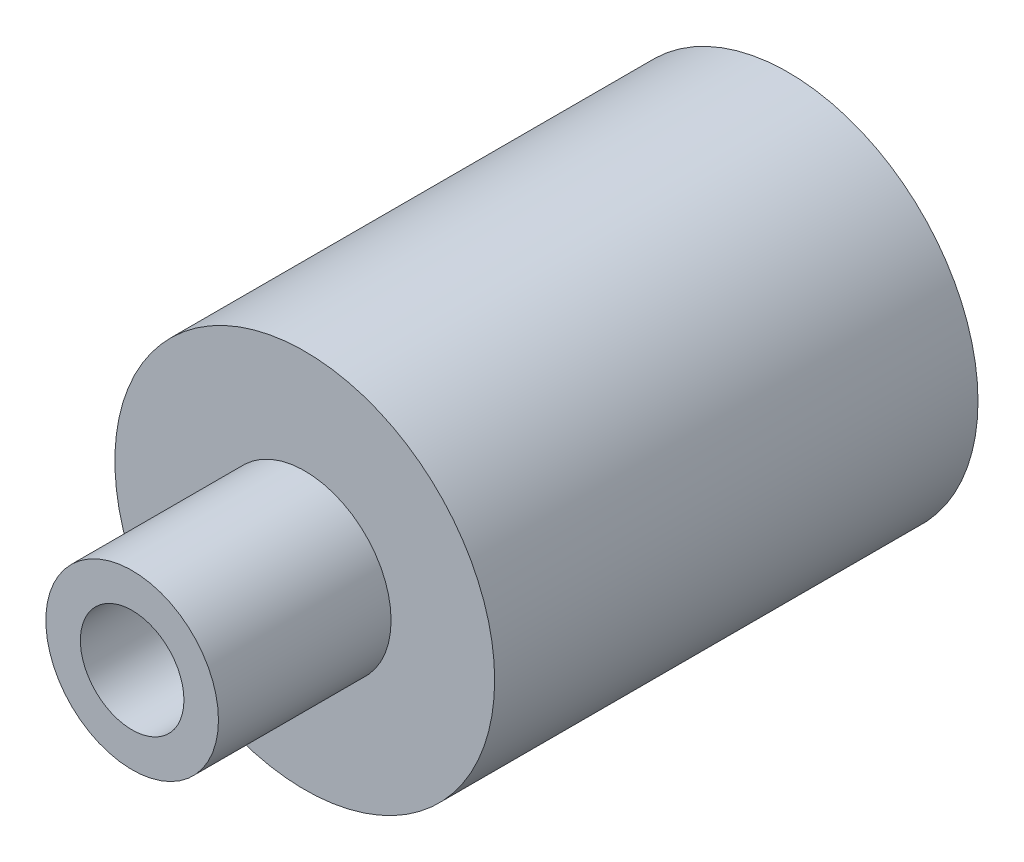
SolidWorks part; units mm, degrees
ref_plane "Спереди" through (0, 0, 0) normal (0, 0, 1) x (1, 0, 0)
ref_plane "Сверху" through (0, 0, 0) normal (0, 1, 0) x (1, 0, 0)
ref_plane "Справа" through (0, 0, 0) normal (1, 0, 0) x (0, 0, -1)
sketch "Эскиз1" plane through (0, 0, 0) normal (1, 0, 0) x (0, 0, -1)
  line L0 (-28.643, 0) -> (42.3762, 0) construction
  line L1 (28, 11) -> (0, 11)
  line L2 (28, 10) -> (23, 10)
  line L3 (28, 11) -> (28, 10)
  line L4 (2, 8) -> (23, 8)
  line L5 (23, 8) -> (23, 10)
  line L6 (-10, 5) -> (0, 5)
  line L7 (-10, 3) -> (2, 3)
  line L8 (0, 11) -> (0, 5)
  line L9 (2, 8) -> (2, 3)
  line L10 (-10, 3) -> (-10, 5)
  dimension "D1" = 28
  dimension "D2" = 22
  dimension "D3" = 20
  dimension "D4" = 2
  dimension "D5" = 5
  dimension "D6" = 10
  dimension "D7" = 6
  dimension "D8" = 10
  dimension "D9" = 2
revolve "Повернуть1" add sketch "Эскиз1" angle 360 about L0
